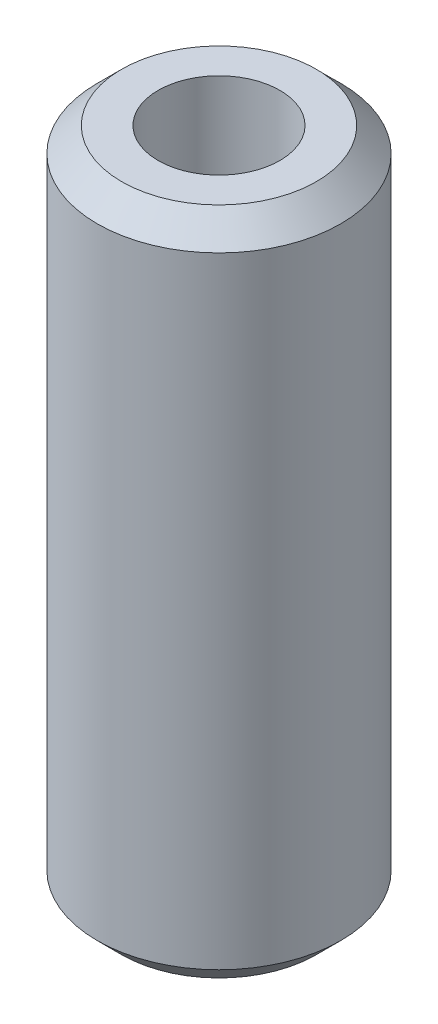
SolidWorks part; units mm, degrees
ref_plane "Front Plane" through (0, 0, 0) normal (0, 0, 1) x (1, 0, 0)
ref_plane "Top Plane" through (0, 0, 0) normal (0, 1, 0) x (1, 0, 0)
ref_plane "Right Plane" through (0, 0, 0) normal (1, 0, 0) x (0, 0, -1)
sketch "Sketch1" plane through (0, 0, 0) normal (0, 1, 0) x (1, 0, 0)
  circle A0 centre (0, 0) radius 6.35
  circle A1 centre (0, 0) radius 12.7
  dimension "D1" = 12.7
  dimension "D2" = 25.4
extrude "Boss-Extrude1" add sketch "Sketch1" along normal mid plane 69.85
chamfer "Chamfer1" distance 2.54 angle 45 2 edges at (0, -34.925, 12.7) (0, 34.925, 12.7)
